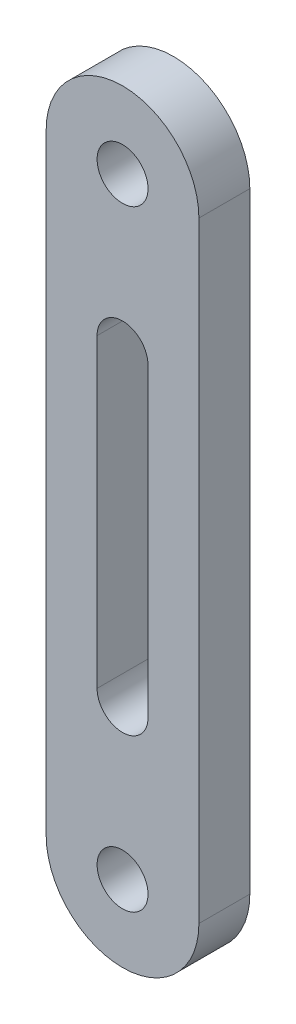
SolidWorks part; units mm, degrees
ref_plane "Alzado" through (0, 0, 0) normal (0, 0, 1) x (1, 0, 0)
ref_plane "Planta" through (0, 0, 0) normal (0, 1, 0) x (1, 0, 0)
ref_plane "Vista lateral" through (0, 0, 0) normal (1, 0, 0) x (0, 0, -1)
sketch "Model" plane through (0, 0, 0) normal (0, 0, 1) x (1, 0, 0)
  line L0 (213.2508, 152.4285) -> (213.2508, 188.4285)
  line L1 (204.2508, 188.4285) -> (204.2508, 152.4285)
  line L2 (207.2508, 179.4285) -> (207.2508, 161.4285)
  line L3 (210.2508, 161.4285) -> (210.2508, 179.4285)
  circle A0 centre (208.7508, 188.4285) radius 1.5
  circle A1 centre (208.7508, 152.4285) radius 1.5
  arc A2 (204.2508, 152.4285) -> (213.2508, 152.4285) centre (208.7508, 152.4285) ccw
  arc A3 (213.2508, 188.4285) -> (204.2508, 188.4285) centre (208.7508, 188.4285) ccw
  arc A4 (207.2508, 161.4285) -> (210.2508, 161.4285) centre (208.7508, 161.4285) ccw
  arc A5 (210.2508, 179.4285) -> (207.2508, 179.4285) centre (208.7508, 179.4285) ccw
extrude "Saliente-Extruir1" add sketch "Model" along normal blind 3
